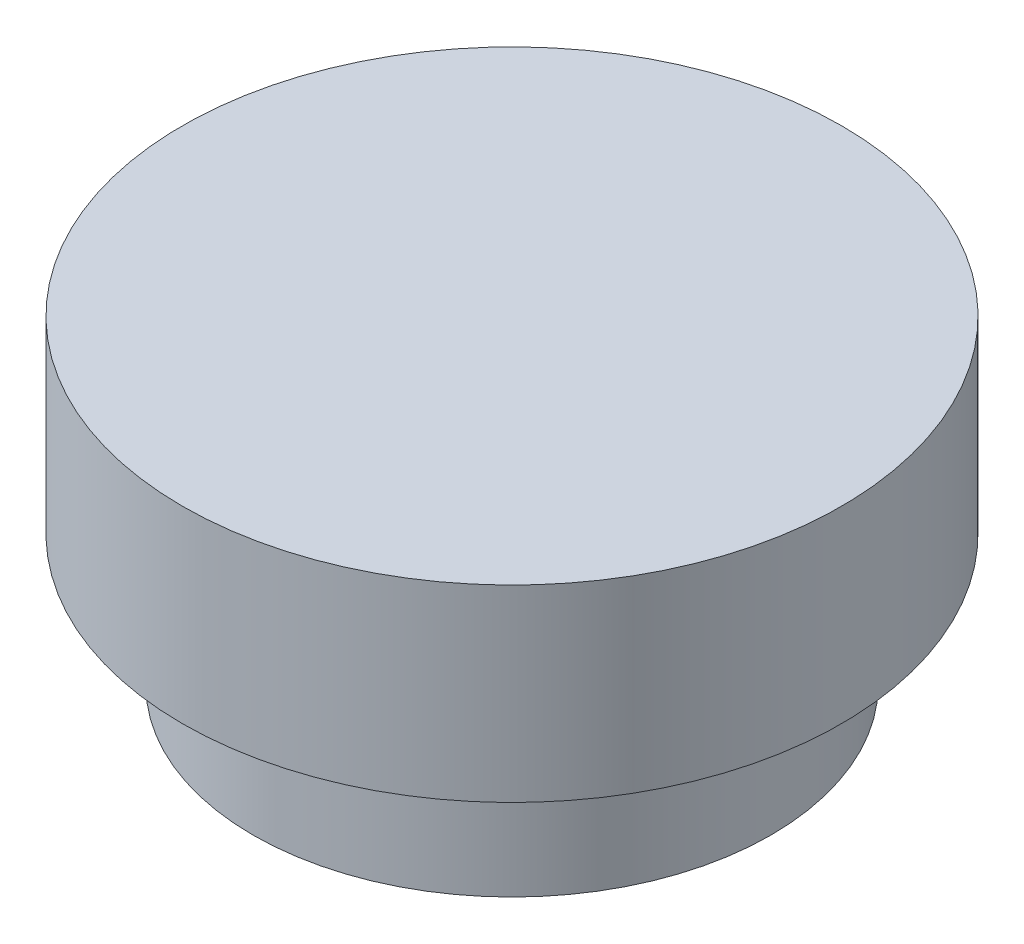
SolidWorks part; units mm, degrees
ref_plane "Front Plane" through (0, 0, 0) normal (0, 0, 1) x (1, 0, 0)
ref_plane "Top Plane" through (0, 0, 0) normal (0, 1, 0) x (1, 0, 0)
ref_plane "Right Plane" through (0, 0, 0) normal (1, 0, 0) x (0, 0, -1)
sketch "Sketch1" plane through (0, 0, 0) normal (0, 1, 0) x (1, 0, 0)
  circle A0 centre (0, 0) radius 5
  dimension "D1" = 10
extrude "Boss-Extrude1" add sketch "Sketch1" along normal blind 10 contours A0
sketch "Sketch2" plane through (0, 10, 0) normal (0, 1, 0) x (1, 0, 0)
  circle A0 centre (0, 0) radius 27.5
  dimension "D1" = 55
extrude "Boss-Extrude2" add sketch "Sketch2" along normal blind 14
sketch "Sketch3" plane through (0, 24, 0) normal (0, 1, 0) x (1, 0, 0)
  circle A0 centre (0, 0) radius 35
  dimension "D1" = 70
extrude "Boss-Extrude3" add sketch "Sketch3" along normal blind 20
